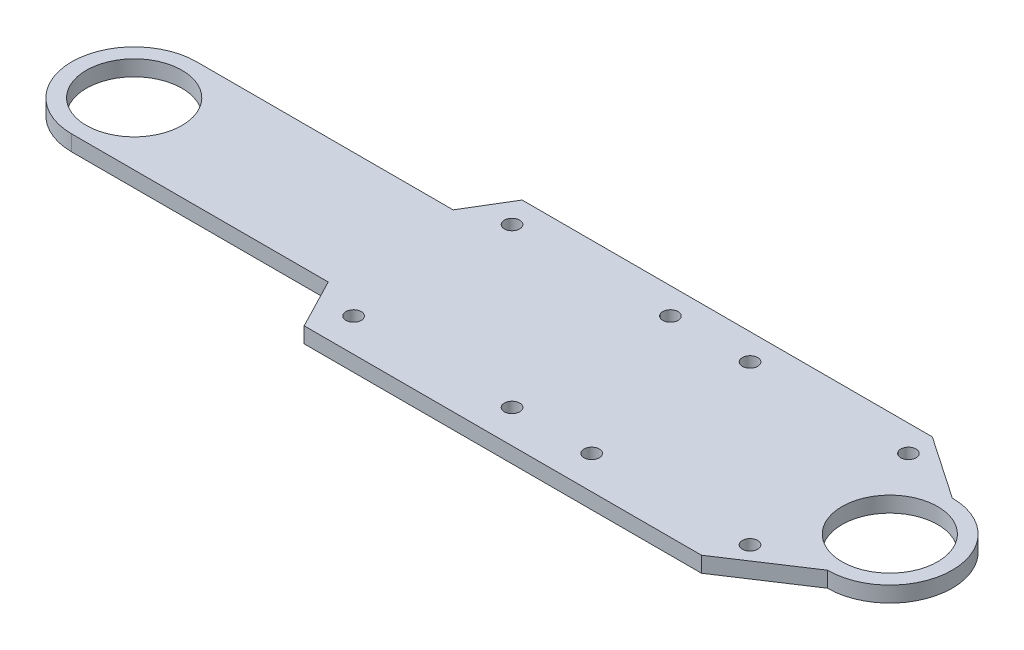
SolidWorks part; units mm, degrees
ref_plane "Front" through (0, 0, 0) normal (0, 0, 1) x (1, 0, 0)
ref_plane "Top" through (0, 0, 0) normal (0, 1, 0) x (1, 0, 0)
ref_plane "Right" through (0, 0, 0) normal (1, 0, 0) x (0, 0, -1)
sketch "Sketch5" plane through (0, 0, 0) normal (1, 0, 0) x (0, 0, -1)
  line L1 (25.34, 1.53) -> (-25.34, 1.53)
  line L2 (25.34, 1.53) -> (25.34, -1.53)
  line L3 (25.34, -1.53) -> (-25.34, -1.53)
  line L4 (-25.34, 1.53) -> (-25.34, -1.53)
extrude "Extrude2" add sketch "Sketch5" along normal blind 180
sketch "Sketch6" plane through (0, 1.53, 0) normal (0, 1, 0) x (-1, 0, 0)
  line L0 (-163.76, 12.2238) -> (-148.9, 22.005)
  line L1 (-71.1472, 22.005) -> (-71.1472, 25.34)
  line L2 (-71.1472, 22.005) -> (-66.0755, 12.2238)
  line L3 (-66.0755, 12.2238) -> (-15.875, 12.2238)
  line L4 (-15.875, -12.2238) -> (-66.0755, -12.2238)
  line L5 (-66.0755, -12.2238) -> (-71.1472, -20.64)
  line L6 (-71.1472, -20.64) -> (-151.4371, -20.64)
  line L7 (-151.4371, -20.64) -> (-163.76, -12.2238)
  line L8 (-180, -25.34) -> (-180, 25.34)
  line L9 (-180, 25.34) -> (-148.9, 25.34)
  line L10 (0, 25.34) -> (0, -25.34)
  line L11 (0, -25.34) -> (-180, -25.34)
  line L12 (-148.9, 25.34) -> (-148.9, 22.005)
  line L13 (-180, 25.34) -> (0, 25.34) construction
  line L14 (-71.1472, 25.34) -> (0, 25.34)
  circle A0 centre (-15.875, 0) radius 9.36
  circle A1 centre (-74.32, -15.5) radius 1.5
  circle A2 centre (-74.32, 15.5) radius 1.5
  circle A3 centre (-105.32, -15.5) radius 1.5
  circle A4 centre (-105.32, 15.5) radius 1.5
  circle A5 centre (-120.9, -15.5) radius 1.5
  circle A6 centre (-120.9, 15.5) radius 1.5
  circle A7 centre (-151.9, -15.5) radius 1.5
  circle A8 centre (-151.9, 15.5) radius 1.5
  circle A9 centre (-163.76, 0) radius 9.36
  arc A10 (-163.76, 12.2238) -> (-163.76, -12.2238) centre (-163.76, 0) ccw
  arc A11 (-15.875, 12.2238) -> (-15.875, -12.2238) centre (-15.875, 0) cw
  dimension "D1" = 15.875
  dimension "D2" = 74.32
  dimension "D3" = 151.9
  dimension "D4" = 163.76
  dimension "D5" = 120.9
extrude "Cut-Extrude3" cut sketch "Sketch6" against normal through all
sketch "Sketch7" plane through (0, 1.53, 0) normal (0, 1, 0) x (-1, 0, 0)
  line L1 (-71.1472, 22.005) -> (-148.9, 22.005)
  line L2 (-71.1472, 22.005) -> (-71.1472, 25.34)
  line L3 (-71.1472, 25.34) -> (-148.9, 25.34)
  line L4 (-148.9, 22.005) -> (-148.9, 25.34)
extrude "Cut-Extrude4" cut sketch "Sketch7" against normal through all
